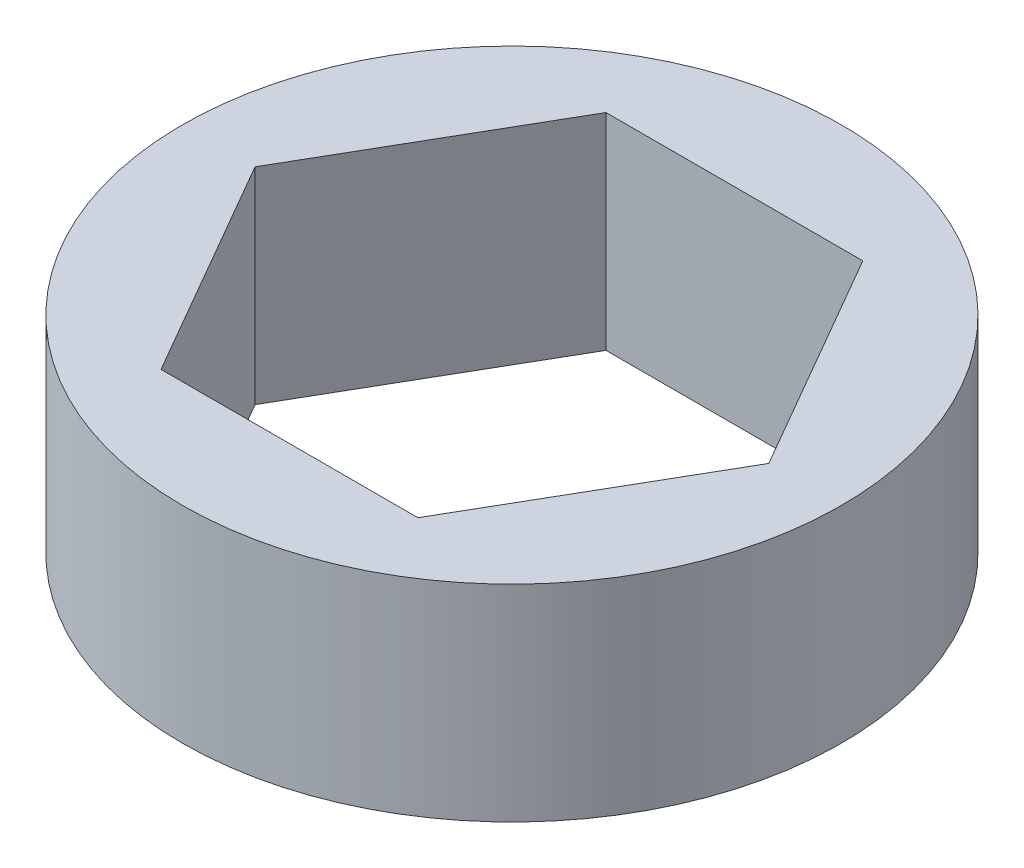
SolidWorks part; units mm, degrees
ref_plane "Front Plane" through (0, 0, 0) normal (0, 0, 1) x (1, 0, 0)
ref_plane "Top Plane" through (0, 0, 0) normal (0, 1, 0) x (1, 0, 0)
ref_plane "Right Plane" through (0, 0, 0) normal (1, 0, 0) x (0, 0, -1)
sketch "Sketch1" plane through (0, 0, 0) normal (0, 1, 0) x (1, 0, 0)
  line L1 (7.9189, 0) -> (3.9595, 6.858)
  line L2 (3.9595, 6.858) -> (-3.9595, 6.858)
  line L3 (-3.9595, 6.858) -> (-7.9189, 0)
  line L4 (-7.9189, 0) -> (-3.9595, -6.858)
  line L5 (-3.9595, -6.858) -> (3.9595, -6.858)
  line L6 (3.9595, -6.858) -> (7.9189, 0)
  circle A0 centre (0, 0) radius 6.858 construction
  circle A1 centre (0, 0) radius 10.16
  dimension "D2" = 20.32
  dimension "D1" = 13.716
extrude "Boss-Extrude1" add sketch "Sketch1" along normal blind 6.35
